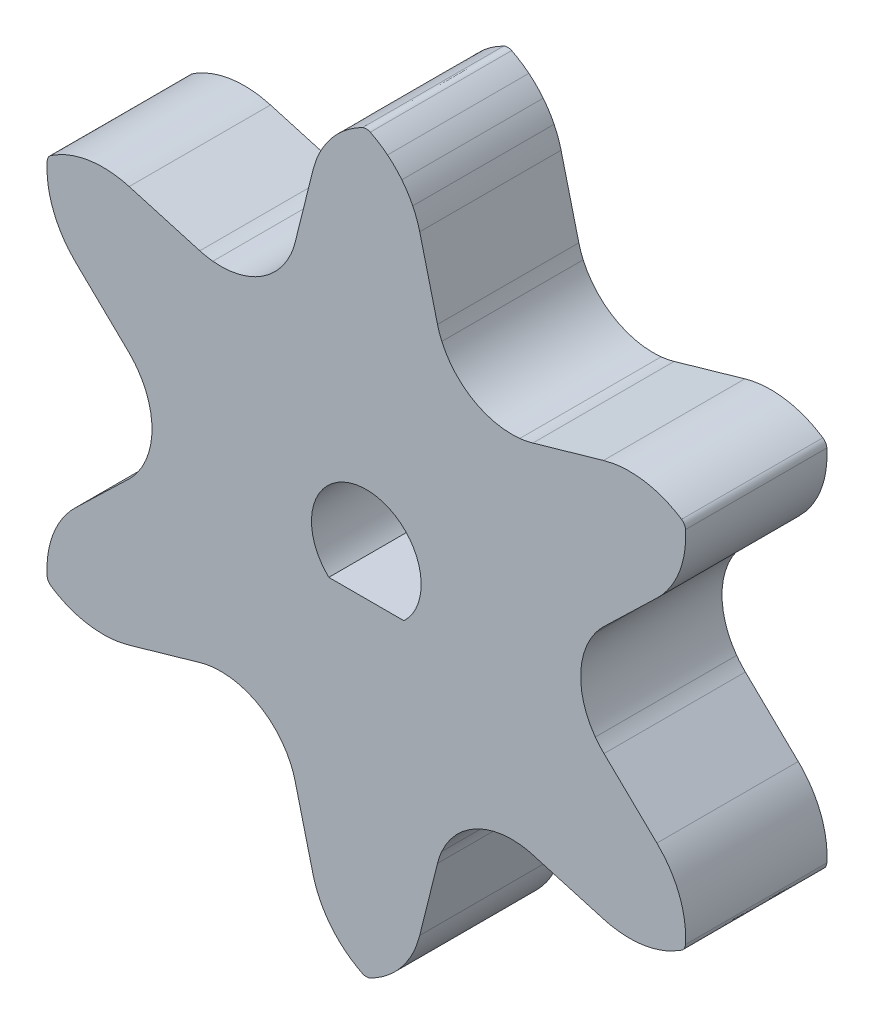
SolidWorks part; units mm, degrees
ref_plane "Front Plane" through (0, 0, 0) normal (0, 0, 1) x (1, 0, 0)
ref_plane "Top Plane" through (0, 0, 0) normal (0, 1, 0) x (1, 0, 0)
ref_plane "Right Plane" through (0, 0, 0) normal (1, 0, 0) x (0, 0, -1)
sketch "Sketch1" plane through (0, 0, 0) normal (0, 0, 1) x (1, 0, 0)
  arc B0 (-8.9081, -12.6618) -> (-7.243, -14.7357) centre (-5.8274, -11.8937) ccw
  line B1 (-8.4226, -3.8706) -> (-5.7958, -3.8706)
  arc B2 (-5.7958, -3.8706) -> (-8.4226, -3.8706) centre (-7.1092, -2.3956) ccw
  arc B3 (-17.8629, 3.6586) -> (-16.8994, 1.1795) centre (-14.6939, 3.4635) ccw
  line B4 (-5.3103, -12.6618) -> (-4.7111, -10.2584)
  line B5 (-9.5073, -10.2584) -> (-8.9081, -12.6618)
  line B6 (2.681, -5.9708) -> (0.8992, -4.2502)
  line B7 (-1.4989, -8.4039) -> (0.8821, -9.0866)
  line B8 (0.8821, 4.2953) -> (-1.4989, 3.6126)
  line B9 (0.8992, -0.5411) -> (2.681, 1.1795)
  line B10 (-8.9081, 7.8705) -> (-9.5073, 5.4671)
  line B11 (-4.7111, 5.4671) -> (-5.3103, 7.8705)
  line B12 (-16.8994, 1.1795) -> (-15.1176, -0.5411)
  line B13 (-12.7195, 3.6126) -> (-15.1005, 4.2953)
  line B14 (-15.1005, -9.0866) -> (-12.7195, -8.4039)
  line B15 (-15.1176, -4.2502) -> (-16.8994, -5.9708)
  arc B16 (-9.6527, -9.8356) -> (-12.2807, -8.3184) centre (-12.0089, -10.8821) ccw
  arc B17 (-4.5657, -9.8356) -> (-4.7111, -10.2584) centre (-2.2095, -10.8821) ccw
  arc B18 (-6.9755, -14.7357) -> (-5.3103, -12.6618) centre (-8.391, -11.8937) ccw
  arc B19 (-7.243, -14.7357) -> (-6.9755, -14.7357) centre (-7.1092, -14.4671) ccw
  arc B20 (-9.5073, -10.2584) -> (-9.6527, -9.8356) centre (-12.0089, -10.8821) ccw
  arc B21 (-1.9377, -8.3184) -> (-4.5657, -9.8356) centre (-2.2095, -10.8821) ccw
  arc B22 (0.6058, -3.9129) -> (0.8992, -4.2502) centre (2.6901, -2.3956) ccw
  arc B23 (3.6445, -8.4498) -> (2.681, -5.9708) centre (0.4755, -8.2547) ccw
  arc B24 (3.5107, -8.6815) -> (3.6445, -8.4498) centre (3.345, -8.4314) ccw
  arc B25 (0.8821, -9.0866) -> (3.5107, -8.6815) centre (1.7572, -6.0346) ccw
  arc B26 (-1.4989, -8.4039) -> (-1.9377, -8.3184) centre (-2.2095, -10.8821) ccw
  arc B27 (0.6058, -0.8784) -> (0.6058, -3.9129) centre (2.6901, -2.3956) ccw
  arc B28 (-1.9377, 3.5271) -> (-1.4989, 3.6126) centre (-2.2095, 6.0908) ccw
  arc B29 (3.5107, 3.8902) -> (0.8821, 4.2953) centre (1.7572, 1.2433) ccw
  arc B30 (3.6445, 3.6586) -> (3.5107, 3.8902) centre (3.345, 3.6401) ccw
  arc B31 (2.681, 1.1795) -> (3.6445, 3.6586) centre (0.4755, 3.4635) ccw
  arc B32 (0.8992, -0.5411) -> (0.6058, -0.8784) centre (2.6901, -2.3956) ccw
  arc B33 (-4.5657, 5.0444) -> (-1.9377, 3.5271) centre (-2.2095, 6.0908) ccw
  arc B34 (-9.6527, 5.0444) -> (-9.5073, 5.4671) centre (-12.0089, 6.0908) ccw
  arc B35 (-7.243, 9.9444) -> (-8.9081, 7.8705) centre (-5.8274, 7.1024) ccw
  arc B36 (-6.9755, 9.9444) -> (-7.243, 9.9444) centre (-7.1092, 9.6759) ccw
  arc B37 (-5.3103, 7.8705) -> (-6.9755, 9.9444) centre (-8.391, 7.1024) ccw
  arc B38 (-4.7111, 5.4671) -> (-4.5657, 5.0444) centre (-2.2095, 6.0908) ccw
  arc B39 (-12.2807, 3.5271) -> (-9.6527, 5.0444) centre (-12.0089, 6.0908) ccw
  arc B40 (-14.8242, -3.9129) -> (-14.8242, -0.8784) centre (-16.9085, -2.3956) ccw
  arc B41 (-14.8242, -0.8784) -> (-15.1176, -0.5411) centre (-16.9085, -2.3956) ccw
  arc B42 (-17.7291, 3.8902) -> (-17.8629, 3.6586) centre (-17.5634, 3.6401) ccw
  arc B43 (-15.1005, 4.2953) -> (-17.7291, 3.8902) centre (-15.9757, 1.2433) ccw
  arc B44 (-12.7195, 3.6126) -> (-12.2807, 3.5271) centre (-12.0089, 6.0908) ccw
  arc B45 (-12.2807, -8.3184) -> (-12.7195, -8.4039) centre (-12.0089, -10.8821) ccw
  arc B46 (-17.7291, -8.6815) -> (-15.1005, -9.0866) centre (-15.9757, -6.0346) ccw
  arc B47 (-17.8629, -8.4498) -> (-17.7291, -8.6815) centre (-17.5634, -8.4314) ccw
  arc B48 (-16.8994, -5.9708) -> (-17.8629, -8.4498) centre (-14.6939, -8.2547) ccw
  arc B49 (-15.1176, -4.2502) -> (-14.8242, -3.9129) centre (-16.9085, -2.3956) ccw
  arc B50 (0.6058, -0.8784) -> (0.6058, -3.9129) centre (2.6901, -2.3956) ccw
  arc B51 (-4.5657, 5.0444) -> (-1.9377, 3.5271) centre (-2.2095, 6.0908) ccw
  arc B52 (-9.6527, -9.8356) -> (-12.2807, -8.3184) centre (-12.0089, -10.8821) ccw
  arc B53 (-12.2807, 3.5271) -> (-9.6527, 5.0444) centre (-12.0089, 6.0908) ccw
  arc B54 (-1.9377, -8.3184) -> (-4.5657, -9.8356) centre (-2.2095, -10.8821) ccw
  arc B55 (-14.8242, -3.9129) -> (-14.8242, -0.8784) centre (-16.9085, -2.3956) ccw
  spline B56 degree 3 poles (0.8992, -4.2502) (0.7918, -4.1464) (0.6939, -4.034) (0.6058, -3.9129) knots 0 0 0 0 1 1 1 1
  spline B57 degree 3 poles (2.681, -5.9708) (2.0875, -5.3976) (1.4936, -4.8242) (0.8992, -4.2502) knots 0 0 0 0 1 1 1 1
  spline B58 degree 3 poles (3.6445, -8.4498) (3.6587, -8.2186) (3.6476, -7.9903) (3.5773, -7.5395) (3.5167, -7.3147) (3.3512, -6.8899) (3.2466, -6.6883) (2.9931, -6.3068) (2.846, -6.1301) (2.681, -5.9708) knots 0 0 0 0 0.25 0.25 0.5 0.5 0.75 0.75 1 1 1 1
  spline B59 degree 3 poles (3.6445, -8.4498) (3.6387, -8.5427) (3.5883, -8.6301) (3.5107, -8.6815) knots 0 0 0 0 1 1 1 1
  spline B60 degree 3 poles (0.8821, -9.0866) (1.1026, -9.1498) (1.3261, -9.1884) (1.7791, -9.2176) (2.011, -9.2076) (2.4617, -9.1388) (2.6818, -9.0807) (3.1112, -8.9156) (3.3175, -8.8095) (3.5107, -8.6815) knots 0 0 0 0 0.25 0.25 0.5 0.5 0.75 0.75 1 1 1 1
  spline B61 degree 3 poles (0.8821, -9.0866) (0.089, -8.8592) (-0.7046, -8.6316) (-1.4989, -8.4039) knots 0 0 0 0 1 1 1 1
  spline B62 degree 3 poles (-1.9377, -8.3184) (-1.7887, -8.3342) (-1.6425, -8.3627) (-1.4989, -8.4039) knots 0 0 0 0 1 1 1 1
  spline B63 degree 3 poles (-9.5073, 5.4671) (-9.5435, 5.3222) (-9.5919, 5.1813) (-9.6527, 5.0444) knots 0 0 0 0 1 1 1 1
  spline B64 degree 3 poles (-8.9081, 7.8705) (-9.1077, 7.0699) (-9.3074, 6.2689) (-9.5073, 5.4671) knots 0 0 0 0 1 1 1 1
  spline B65 degree 3 poles (-7.243, 9.9444) (-7.4504, 9.8411) (-7.6425, 9.7174) (-7.9977, 9.4311) (-8.1621, 9.2662) (-8.4472, 8.9105) (-8.5696, 8.7191) (-8.7732, 8.3088) (-8.8526, 8.0931) (-8.9081, 7.8705) knots 0 0 0 0 0.25 0.25 0.5 0.5 0.75 0.75 1 1 1 1
  spline B66 degree 3 poles (-7.243, 9.9444) (-7.1597, 9.9859) (-7.0587, 9.9859) (-6.9755, 9.9444) knots 0 0 0 0 1 1 1 1
  spline B67 degree 3 poles (-5.3103, 7.8705) (-5.3658, 8.0931) (-5.4442, 8.306) (-5.6453, 8.7128) (-5.77, 8.9087) (-6.0549, 9.2647) (-6.2153, 9.4262) (-6.5729, 9.7155) (-6.768, 9.8411) (-6.9755, 9.9444) knots 0 0 0 0 0.25 0.25 0.5 0.5 0.75 0.75 1 1 1 1
  spline B68 degree 3 poles (-5.3103, 7.8705) (-5.1107, 7.0699) (-4.911, 6.2689) (-4.7111, 5.4671) knots 0 0 0 0 1 1 1 1
  spline B69 degree 3 poles (-4.5657, 5.0444) (-4.6265, 5.1813) (-4.6749, 5.3222) (-4.7111, 5.4671) knots 0 0 0 0 1 1 1 1
  spline B70 degree 3 poles (-4.7111, -10.2584) (-4.6749, -10.1135) (-4.6265, -9.9725) (-4.5657, -9.8356) knots 0 0 0 0 1 1 1 1
  spline B71 degree 3 poles (-5.3103, -12.6618) (-5.1107, -11.8612) (-4.911, -11.0602) (-4.7111, -10.2584) knots 0 0 0 0 1 1 1 1
  spline B72 degree 3 poles (-6.9755, -14.7357) (-6.7681, -14.6324) (-6.5759, -14.5087) (-6.2207, -14.2223) (-6.0563, -14.0574) (-5.7712, -13.7018) (-5.6488, -13.5104) (-5.4452, -13.1001) (-5.3658, -12.8843) (-5.3103, -12.6618) knots 0 0 0 0 0.25 0.25 0.5 0.5 0.75 0.75 1 1 1 1
  spline B73 degree 3 poles (-6.9755, -14.7357) (-7.0587, -14.7771) (-7.1597, -14.7771) (-7.243, -14.7357) knots 0 0 0 0 1 1 1 1
  spline B74 degree 3 poles (-8.9081, -12.6618) (-8.8526, -12.8844) (-8.7742, -13.0972) (-8.5731, -13.5041) (-8.4485, -13.7) (-8.1635, -14.0559) (-8.0031, -14.2174) (-7.6455, -14.5067) (-7.4504, -14.6324) (-7.243, -14.7357) knots 0 0 0 0 0.25 0.25 0.5 0.5 0.75 0.75 1 1 1 1
  spline B75 degree 3 poles (-8.9081, -12.6618) (-9.1077, -11.8612) (-9.3074, -11.0602) (-9.5073, -10.2584) knots 0 0 0 0 1 1 1 1
  spline B76 degree 3 poles (-9.6527, -9.8356) (-9.5919, -9.9725) (-9.5435, -10.1135) (-9.5073, -10.2584) knots 0 0 0 0 1 1 1 1
  spline B77 degree 3 poles (-15.1176, -0.5411) (-15.0102, -0.6449) (-14.9124, -0.7572) (-14.8242, -0.8784) knots 0 0 0 0 1 1 1 1
  spline B78 degree 3 poles (-16.8994, 1.1795) (-16.3059, 0.6064) (-15.7121, 0.0329) (-15.1176, -0.5411) knots 0 0 0 0 1 1 1 1
  spline B79 degree 3 poles (-17.8629, 3.6586) (-17.8771, 3.4273) (-17.8661, 3.199) (-17.7957, 2.7482) (-17.7351, 2.5234) (-17.5696, 2.0987) (-17.465, 1.897) (-17.2116, 1.5155) (-17.0644, 1.3389) (-16.8994, 1.1795) knots 0 0 0 0 0.25 0.25 0.5 0.5 0.75 0.75 1 1 1 1
  spline B80 degree 3 poles (-17.8629, 3.6586) (-17.8572, 3.7514) (-17.8067, 3.8388) (-17.7291, 3.8902) knots 0 0 0 0 1 1 1 1
  spline B81 degree 3 poles (-15.1005, 4.2953) (-15.321, 4.3586) (-15.5446, 4.3971) (-15.9975, 4.4264) (-16.2295, 4.4164) (-16.6801, 4.3476) (-16.9002, 4.2894) (-17.3296, 4.1244) (-17.5359, 4.0182) (-17.7291, 3.8902) knots 0 0 0 0 0.25 0.25 0.5 0.5 0.75 0.75 1 1 1 1
  spline B82 degree 3 poles (-15.1005, 4.2953) (-14.3074, 4.0679) (-13.5138, 3.8404) (-12.7195, 3.6126) knots 0 0 0 0 1 1 1 1
  spline B83 degree 3 poles (-12.2807, 3.5271) (-12.4297, 3.5429) (-12.5759, 3.5714) (-12.7195, 3.6126) knots 0 0 0 0 1 1 1 1
  spline B84 degree 3 poles (-1.4989, 3.6126) (-1.6425, 3.5714) (-1.7887, 3.5429) (-1.9377, 3.5271) knots 0 0 0 0 1 1 1 1
  spline B85 degree 3 poles (0.8821, 4.2953) (0.089, 4.0679) (-0.7046, 3.8404) (-1.4989, 3.6126) knots 0 0 0 0 1 1 1 1
  spline B86 degree 3 poles (3.5107, 3.8902) (3.3176, 4.0182) (3.1143, 4.1227) (2.6888, 4.2872) (2.4638, 4.3471) (2.0132, 4.4162) (1.7863, 4.4265) (1.3291, 4.3977) (1.1026, 4.3586) (0.8821, 4.2953) knots 0 0 0 0 0.25 0.25 0.5 0.5 0.75 0.75 1 1 1 1
  spline B87 degree 3 poles (3.5107, 3.8902) (3.5883, 3.8388) (3.6387, 3.7514) (3.6445, 3.6586) knots 0 0 0 0 1 1 1 1
  spline B88 degree 3 poles (2.681, 1.1795) (2.846, 1.3389) (2.9912, 1.5132) (3.243, 1.8908) (3.3503, 2.0967) (3.5161, 2.5214) (3.5757, 2.7411) (3.6475, 3.1955) (3.6587, 3.4273) (3.6445, 3.6586) knots 0 0 0 0 0.25 0.25 0.5 0.5 0.75 0.75 1 1 1 1
  spline B89 degree 3 poles (0.8992, -0.5411) (1.4936, 0.0329) (2.0875, 0.6064) (2.681, 1.1795) knots 0 0 0 0 1 1 1 1
  spline B90 degree 3 poles (0.6058, -0.8784) (0.6939, -0.7572) (0.7918, -0.6449) (0.8992, -0.5411) knots 0 0 0 0 1 1 1 1
  spline B91 degree 3 poles (-15.1005, -9.0866) (-14.3074, -8.8592) (-13.5138, -8.6316) (-12.7195, -8.4039) knots 0 0 0 0 1 1 1 1
  spline B92 degree 3 poles (-17.7291, -8.6815) (-17.536, -8.8094) (-17.3328, -8.914) (-16.9072, -9.0784) (-16.6822, -9.1384) (-16.2316, -9.2075) (-16.0047, -9.2177) (-15.5476, -9.1889) (-15.321, -9.1498) (-15.1005, -9.0866) knots 0 0 0 0 0.25 0.25 0.5 0.5 0.75 0.75 1 1 1 1
  spline B93 degree 3 poles (-17.7291, -8.6815) (-17.8067, -8.6301) (-17.8572, -8.5427) (-17.8629, -8.4498) knots 0 0 0 0 1 1 1 1
  spline B94 degree 3 poles (-16.8994, -5.9708) (-17.0644, -6.1302) (-17.2096, -6.3045) (-17.4614, -6.6821) (-17.5687, -6.888) (-17.7345, -7.3127) (-17.7942, -7.5324) (-17.8659, -7.9867) (-17.8771, -8.2185) (-17.8629, -8.4498) knots 0 0 0 0 0.25 0.25 0.5 0.5 0.75 0.75 1 1 1 1
  spline B95 degree 3 poles (-15.1176, -4.2502) (-15.7121, -4.8242) (-16.3059, -5.3976) (-16.8994, -5.9708) knots 0 0 0 0 1 1 1 1
  spline B96 degree 3 poles (-12.7195, -8.4039) (-12.5759, -8.3627) (-12.4297, -8.3342) (-12.2807, -8.3184) knots 0 0 0 0 1 1 1 1
  spline B97 degree 3 poles (-14.8242, -3.9129) (-14.9124, -4.034) (-15.0102, -4.1464) (-15.1176, -4.2502) knots 0 0 0 0 1 1 1 1
sketch_block_instance "motorsprocket-1"
sketch_block "motorsprocket"
other "DetailItem3"
other "DetailItem4"
extrude "Boss-Extrude1" add sketch "Sketch1" along normal blind 4.7625 contours B40 B97 B15 B48 B93 B46 B14 B96 B16 B76 B5 B0 B74 B73 B18 B4 B70 B21 B62 B7 B25 B59 B23 B6 B56 B27 B90 B9 B31 B87 B29 B8 B84 B33 B69 B11 B37 B67 B66 B35 B10 B63 B39 B83 B13 B43 B80
ref_plane "Plane1" through (-5.7958, -3.8706, 4.7625) normal (1, 0, 0) x (0, 0, -1)
sketch "Sketch4" plane through (0, 0, 4.7625) normal (0, 0, 1) x (1, 0, 0)
  line L12 (-8.4226, -3.8706) -> (-5.7958, -3.8706) construction
  line L13 (-8.4226, -3.8706) -> (-5.7958, -3.8706)
  line L14 (-8.3733, -3.7436) -> (-5.8451, -3.7436)
  arc A24 (-5.7958, -3.8706) -> (-8.4226, -3.8706) centre (-7.1092, -2.3956) ccw construction
  arc A25 (-5.7958, -3.8706) -> (-8.4226, -3.8706) centre (-7.1092, -2.3956) ccw
  arc A26 (-5.8451, -3.7436) -> (-8.3733, -3.7436) centre (-7.1092, -2.3956) ccw
  dimension "D1" = 0.127
extrude "Boss-Extrude2" add sketch "Sketch4" against normal blind 4.7625
